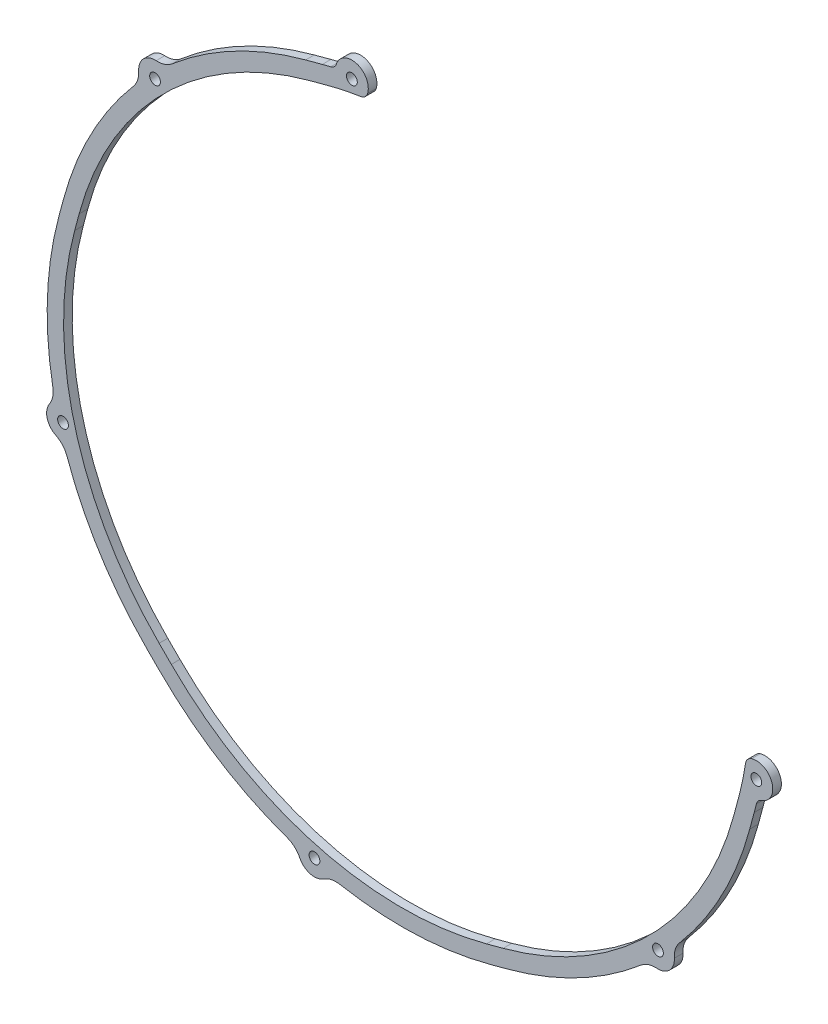
SolidWorks part; units mm, degrees
material "Hexcel AS4C (3000 丝)"
ref_plane "前视基准面" through (0, 0, 0) normal (0, 0, 1) x (1, 0, 0)
ref_plane "上视基准面" through (0, 0, 0) normal (0, 1, 0) x (1, 0, 0)
ref_plane "右视基准面" through (0, 0, 0) normal (1, 0, 0) x (0, 0, -1)
sketch "草图1" plane through (0, 0, 0) normal (0, 0, 1) x (1, 0, 0)
  line L10 (-6.2611, -107.9819) -> (-5.2259, -104.1182)
  line L11 (-7.9304, -103.3935) -> (-8.9657, -107.2573)
  line L12 (-62.4484, -160.7399) -> (-66.3121, -161.7752)
  line L13 (-139.3707, -142.1992) -> (-142.1992, -139.3707)
  line L14 (-161.7752, -66.3121) -> (-160.7399, -62.4484)
  line L15 (-107.2573, -8.9657) -> (-103.3935, -7.9304)
  line L16 (-104.1182, -5.2259) -> (-107.9819, -6.2611)
  line L17 (-163.4445, -61.7237) -> (-164.4798, -65.5874)
  line L18 (-144.1791, -141.3506) -> (-141.3506, -144.1791)
  line L19 (-65.5874, -164.4798) -> (-61.7237, -163.4445)
  line L20 (-6.2611, -107.9819) -> (-5.2259, -104.1182)
  line L21 (-7.9304, -103.3935) -> (-8.9657, -107.2573)
  line L22 (-62.4484, -160.7399) -> (-66.3121, -161.7752)
  line L23 (-139.3707, -142.1992) -> (-142.1992, -139.3707)
  line L24 (-161.7752, -66.3121) -> (-160.7399, -62.4484)
  line L25 (-107.2573, -8.9657) -> (-103.3935, -7.9304)
  line L26 (-104.1182, -5.2259) -> (-107.9819, -6.2611)
  line L27 (-163.4445, -61.7237) -> (-164.4798, -65.5874)
  line L28 (-144.1791, -141.3506) -> (-141.3506, -144.1791)
  line L29 (-65.5874, -164.4798) -> (-61.7237, -163.4445)
  circle A1 centre (-97.5152, -3.7585) radius 1.25
  circle A2 centre (-97.5152, -3.7585) radius 1.25
  circle A3 centre (-164.4798, -106.1888) radius 1.25
  circle A4 centre (-164.4798, -106.1888) radius 1.25
  circle A5 centre (-106.1888, -164.4798) radius 1.25
  circle A6 centre (-106.1888, -164.4798) radius 1.25
  circle A7 centre (-26.5618, -143.1438) radius 1.25
  circle A8 centre (-26.5618, -143.1438) radius 1.25
  circle A9 centre (-3.7585, -97.5152) radius 1.25
  circle A10 centre (-3.7585, -97.5152) radius 1.25
  circle A11 centre (-143.1438, -26.5618) radius 1.25
  circle A12 centre (-143.1438, -26.5618) radius 1.25
  arc A44 (-26.7497, -145.9375) -> (-23.7681, -142.9559) centre (-26.5618, -143.1438) ccw
  arc A45 (-22.3073, -138.5345) -> (-23.7681, -142.9559) centre (-17.6022, -142.5412) ccw
  arc A46 (-22.3073, -138.5345) -> (-6.2611, -107.9819) centre (-82.0244, -87.6812) ccw
  arc A47 (-5.2259, -104.1182) -> (-4.7329, -102.1799) centre (-80.9891, -83.8175) ccw
  arc A48 (-2.8846, -100.1753) -> (-4.7329, -102.1799) centre (-2.0107, -102.8354) ccw
  arc A49 (-2.8846, -100.1753) -> (-6.5155, -97.0262) centre (-3.7585, -97.5152) ccw
  arc A50 (-7.9304, -103.3935) -> (-6.5155, -97.0262) centre (-80.9891, -83.8175) ccw
  arc A51 (-62.4484, -160.7399) -> (-8.9657, -107.2573) centre (-82.0244, -87.6812) ccw
  arc A52 (-139.3707, -142.1992) -> (-66.3121, -161.7752) centre (-85.8881, -88.7165) ccw
  arc A53 (-161.7752, -66.3121) -> (-142.1992, -139.3707) centre (-88.7165, -85.8881) ccw
  arc A54 (-107.2573, -8.9657) -> (-160.7399, -62.4484) centre (-87.6812, -82.0244) ccw
  arc A55 (-97.0262, -6.5155) -> (-103.3935, -7.9304) centre (-83.8175, -80.9891) ccw
  arc A56 (-97.0262, -6.5155) -> (-100.1753, -2.8846) centre (-97.5152, -3.7585) ccw
  arc A57 (-102.1799, -4.7329) -> (-100.1753, -2.8846) centre (-102.8354, -2.0107) ccw
  arc A58 (-102.1799, -4.7329) -> (-104.1182, -5.2259) centre (-83.8175, -80.9891) ccw
  arc A59 (-107.9819, -6.2611) -> (-138.5345, -22.3073) centre (-87.6812, -82.0244) ccw
  arc A60 (-142.9559, -23.7681) -> (-138.5345, -22.3073) centre (-142.5412, -17.6022) ccw
  arc A61 (-142.9559, -23.7681) -> (-145.9375, -26.7497) centre (-143.1438, -26.5618) ccw
  arc A62 (-147.3984, -31.1711) -> (-145.9375, -26.7497) centre (-152.1034, -27.1645) ccw
  arc A63 (-147.3984, -31.1711) -> (-163.4445, -61.7237) centre (-87.6812, -82.0244) ccw
  arc A64 (-164.4798, -65.5874) -> (-165.8597, -100.0697) centre (-88.7165, -85.8881) ccw
  arc A65 (-166.8052, -104.6292) -> (-165.8597, -100.0697) centre (-171.9377, -101.1871) ccw
  arc A66 (-166.8052, -104.6292) -> (-165.7139, -108.7022) centre (-164.4798, -106.1888) ccw
  arc A67 (-162.6153, -112.178) -> (-165.7139, -108.7022) centre (-168.4377, -114.2494) ccw
  arc A68 (-162.6153, -112.178) -> (-144.1791, -141.3506) centre (-88.7165, -85.8881) ccw
  arc A69 (-141.3506, -144.1791) -> (-112.178, -162.6153) centre (-85.8881, -88.7165) ccw
  arc A70 (-108.7022, -165.7139) -> (-112.178, -162.6153) centre (-114.2494, -168.4377) ccw
  arc A71 (-108.7022, -165.7139) -> (-104.6292, -166.8052) centre (-106.1888, -164.4798) ccw
  arc A72 (-100.0697, -165.8597) -> (-104.6292, -166.8052) centre (-101.1871, -171.9377) ccw
  arc A73 (-100.0697, -165.8597) -> (-65.5874, -164.4798) centre (-85.8881, -88.7165) ccw
  arc A74 (-61.7237, -163.4445) -> (-31.1711, -147.3984) centre (-82.0244, -87.6812) ccw
  arc A75 (-26.7497, -145.9375) -> (-31.1711, -147.3984) centre (-27.1645, -152.1034) ccw
  arc A76 (-26.7497, -145.9375) -> (-23.7681, -142.9559) centre (-26.5618, -143.1438) ccw
  arc A77 (-22.3073, -138.5345) -> (-23.7681, -142.9559) centre (-17.6022, -142.5412) ccw
  arc A78 (-22.3073, -138.5345) -> (-6.2611, -107.9819) centre (-82.0244, -87.6812) ccw
  arc A79 (-5.2259, -104.1182) -> (-4.7329, -102.1799) centre (-80.9891, -83.8175) ccw
  arc A80 (-2.8846, -100.1753) -> (-4.7329, -102.1799) centre (-2.0107, -102.8354) ccw
  arc A81 (-2.8846, -100.1753) -> (-6.5155, -97.0262) centre (-3.7585, -97.5152) ccw
  arc A82 (-7.9304, -103.3935) -> (-6.5155, -97.0262) centre (-80.9891, -83.8175) ccw
  arc A83 (-62.4484, -160.7399) -> (-8.9657, -107.2573) centre (-82.0244, -87.6812) ccw
  arc A84 (-139.3707, -142.1992) -> (-66.3121, -161.7752) centre (-85.8881, -88.7165) ccw
  arc A85 (-161.7752, -66.3121) -> (-142.1992, -139.3707) centre (-88.7165, -85.8881) ccw
  arc A86 (-107.2573, -8.9657) -> (-160.7399, -62.4484) centre (-87.6812, -82.0244) ccw
  arc A87 (-97.0262, -6.5155) -> (-103.3935, -7.9304) centre (-83.8175, -80.9891) ccw
  arc A88 (-97.0262, -6.5155) -> (-100.1753, -2.8846) centre (-97.5152, -3.7585) ccw
  arc A89 (-102.1799, -4.7329) -> (-100.1753, -2.8846) centre (-102.8354, -2.0107) ccw
  arc A90 (-102.1799, -4.7329) -> (-104.1182, -5.2259) centre (-83.8175, -80.9891) ccw
  arc A91 (-107.9819, -6.2611) -> (-138.5345, -22.3073) centre (-87.6812, -82.0244) ccw
  arc A92 (-142.9559, -23.7681) -> (-138.5345, -22.3073) centre (-142.5412, -17.6022) ccw
  arc A93 (-142.9559, -23.7681) -> (-145.9375, -26.7497) centre (-143.1438, -26.5618) ccw
  arc A94 (-147.3984, -31.1711) -> (-145.9375, -26.7497) centre (-152.1034, -27.1645) ccw
  arc A95 (-147.3984, -31.1711) -> (-163.4445, -61.7237) centre (-87.6812, -82.0244) ccw
  arc A96 (-164.4798, -65.5874) -> (-165.8597, -100.0697) centre (-88.7165, -85.8881) ccw
  arc A97 (-166.8052, -104.6292) -> (-165.8597, -100.0697) centre (-171.9377, -101.1871) ccw
  arc A98 (-166.8052, -104.6292) -> (-165.7139, -108.7022) centre (-164.4798, -106.1888) ccw
  arc A99 (-162.6153, -112.178) -> (-165.7139, -108.7022) centre (-168.4377, -114.2494) ccw
  arc A100 (-162.6153, -112.178) -> (-144.1791, -141.3506) centre (-88.7165, -85.8881) ccw
  arc A101 (-141.3506, -144.1791) -> (-112.178, -162.6153) centre (-85.8881, -88.7165) ccw
  arc A102 (-108.7022, -165.7139) -> (-112.178, -162.6153) centre (-114.2494, -168.4377) ccw
  arc A103 (-108.7022, -165.7139) -> (-104.6292, -166.8052) centre (-106.1888, -164.4798) ccw
  arc A104 (-100.0697, -165.8597) -> (-104.6292, -166.8052) centre (-101.1871, -171.9377) ccw
  arc A105 (-100.0697, -165.8597) -> (-65.5874, -164.4798) centre (-85.8881, -88.7165) ccw
  arc A106 (-61.7237, -163.4445) -> (-31.1711, -147.3984) centre (-82.0244, -87.6812) ccw
  arc A107 (-26.7497, -145.9375) -> (-31.1711, -147.3984) centre (-27.1645, -152.1034) ccw
  dimension "D1" = 0
  dimension "D2" = 0
  dimension "D3" = 0
  dimension "D4" = 0
  dimension "D5" = 0
  dimension "D6" = 0
  dimension "D7" = 0
extrude "凸台-拉伸1" add sketch "草图1" along normal blind 2
sketch "草图2" plane through (0, 0, 0) normal (0, 0, -1) x (-1, 0, 0)
  line L0 (4.2599, -104.3771) -> (5.2952, -108.2408)
  line L1 (9.9316, -106.9984) -> (8.8964, -103.1347) construction
  line L2 (66.5709, -160.8093) -> (62.7072, -159.774) construction
  line L3 (141.4921, -138.6636) -> (138.6636, -141.4921) construction
  line L4 (159.774, -62.7072) -> (160.8093, -66.5709) construction
  line L5 (103.1347, -8.8964) -> (106.9984, -9.9316) construction
  line L6 (108.2408, -5.2952) -> (104.3771, -4.2599)
  line L7 (165.4457, -65.3286) -> (164.4104, -61.4649)
  line L8 (142.0578, -144.8862) -> (144.8862, -142.0578)
  line L9 (61.4649, -164.4104) -> (65.3286, -165.4457)
  line L10 (61.7237, -163.4445) -> (65.5874, -164.4798)
  line L11 (141.3506, -144.1791) -> (144.1791, -141.3506)
  line L12 (164.4798, -65.5874) -> (163.4445, -61.7237)
  line L13 (107.9819, -6.2611) -> (104.1182, -5.2259)
  line L14 (103.3935, -7.9304) -> (107.2573, -8.9657)
  line L15 (160.7399, -62.4484) -> (161.7752, -66.3121)
  line L16 (142.1992, -139.3707) -> (139.3707, -142.1992)
  line L17 (66.3121, -161.7752) -> (62.4484, -160.7399)
  line L18 (8.9657, -107.2573) -> (7.9304, -103.3935)
  line L19 (5.2259, -104.1182) -> (6.2611, -107.9819)
  line L20 (61.7237, -163.4445) -> (65.5874, -164.4798) construction
  line L21 (141.3506, -144.1791) -> (144.1791, -141.3506) construction
  line L22 (164.4798, -65.5874) -> (163.4445, -61.7237) construction
  line L23 (107.9819, -6.2611) -> (104.1182, -5.2259) construction
  line L24 (103.3935, -7.9304) -> (107.2573, -8.9657) construction
  line L25 (160.7399, -62.4484) -> (161.7752, -66.3121) construction
  line L26 (142.1992, -139.3707) -> (139.3707, -142.1992) construction
  line L27 (66.3121, -161.7752) -> (62.4484, -160.7399) construction
  line L28 (8.9657, -107.2573) -> (7.9304, -103.3935) construction
  line L29 (5.2259, -104.1182) -> (6.2611, -107.9819) construction
  line L30 (7.9304, -103.3935) -> (8.9657, -107.2573) construction
  line L31 (62.4484, -160.7399) -> (66.3121, -161.7752) construction
  line L32 (139.3707, -142.1992) -> (142.1992, -139.3707) construction
  line L33 (161.7752, -66.3121) -> (160.7399, -62.4484) construction
  line L34 (107.2573, -8.9657) -> (103.3935, -7.9304) construction
  line L35 (7.9304, -103.3935) -> (8.9657, -107.2573)
  line L36 (62.4484, -160.7399) -> (66.3121, -161.7752)
  line L37 (139.3707, -142.1992) -> (142.1992, -139.3707)
  line L38 (161.7752, -66.3121) -> (160.7399, -62.4484)
  line L39 (107.2573, -8.9657) -> (103.3935, -7.9304)
  circle A1 centre (97.5152, -3.7585) radius 1.25
  circle A2 centre (97.5152, -3.7585) radius 1.25
  circle A3 centre (164.4798, -106.1888) radius 1.25
  circle A4 centre (164.4798, -106.1888) radius 1.25
  circle A5 centre (106.1888, -164.4798) radius 1.25
  circle A6 centre (106.1888, -164.4798) radius 1.25
  circle A7 centre (26.5618, -143.1438) radius 1.25
  circle A8 centre (26.5618, -143.1438) radius 1.25
  circle A9 centre (3.7585, -97.5152) radius 1.25
  circle A10 centre (3.7585, -97.5152) radius 1.25
  circle A11 centre (143.1438, -26.5618) radius 1.25
  circle A12 centre (143.1438, -26.5618) radius 1.25
  arc A13 (30.5228, -148.1597) -> (26.8169, -146.9352) centre (27.1645, -152.1034) ccw
  arc A14 (22.7704, -142.8888) -> (26.8169, -146.9352) centre (26.5618, -143.1438) ccw
  arc A15 (22.7704, -142.8888) -> (21.5459, -139.1828) centre (17.6022, -142.5412) ccw
  arc A16 (5.2952, -108.2408) -> (21.5459, -139.1828) centre (82.0244, -87.6812) ccw
  arc A17 (3.7607, -102.4141) -> (4.2599, -104.3771) centre (80.9891, -83.8175) ccw
  arc A18 (3.7607, -102.4141) -> (2.5725, -101.1254) centre (2.0107, -102.8354) ccw
  arc A19 (7.5001, -96.8516) -> (2.5725, -101.1254) centre (3.7585, -97.5152) ccw construction
  arc A20 (7.5001, -96.8516) -> (8.8964, -103.1347) centre (80.9891, -83.8175) ccw construction
  arc A21 (9.9316, -106.9984) -> (62.7072, -159.774) centre (82.0244, -87.6812) ccw construction
  arc A22 (66.5709, -160.8093) -> (138.6636, -141.4921) centre (85.8881, -88.7165) ccw construction
  arc A23 (141.4921, -138.6636) -> (160.8093, -66.5709) centre (88.7165, -85.8881) ccw construction
  arc A24 (159.774, -62.7072) -> (106.9984, -9.9316) centre (87.6812, -82.0244) ccw construction
  arc A25 (103.1347, -8.8964) -> (96.8516, -7.5001) centre (83.8175, -80.9891) ccw construction
  arc A26 (101.1254, -2.5725) -> (96.8516, -7.5001) centre (97.5152, -3.7585) ccw construction
  arc A27 (101.1254, -2.5725) -> (102.4141, -3.7607) centre (102.8354, -2.0107) ccw
  arc A28 (104.3771, -4.2599) -> (102.4141, -3.7607) centre (83.8175, -80.9891) ccw
  arc A29 (139.1828, -21.5459) -> (108.2408, -5.2952) centre (87.6812, -82.0244) ccw
  arc A30 (139.1828, -21.5459) -> (142.8888, -22.7704) centre (142.5412, -17.6022) ccw
  arc A31 (146.9352, -26.8169) -> (142.8888, -22.7704) centre (143.1438, -26.5618) ccw
  arc A32 (146.9352, -26.8169) -> (148.1597, -30.5228) centre (152.1034, -27.1645) ccw
  arc A33 (164.4104, -61.4649) -> (148.1597, -30.5228) centre (87.6812, -82.0244) ccw
  arc A34 (166.8432, -100.2505) -> (165.4457, -65.3286) centre (88.7165, -85.8881) ccw
  arc A35 (166.8432, -100.2505) -> (167.6357, -104.0722) centre (171.9377, -101.1871) ccw
  arc A36 (166.1546, -109.5998) -> (167.6357, -104.0722) centre (164.4798, -106.1888) ccw
  arc A37 (166.1546, -109.5998) -> (163.5575, -112.5132) centre (168.4377, -114.2494) ccw
  arc A38 (144.8862, -142.0578) -> (163.5575, -112.5132) centre (88.7165, -85.8881) ccw
  arc A39 (112.5132, -163.5575) -> (142.0578, -144.8862) centre (85.8881, -88.7165) ccw
  arc A40 (112.5132, -163.5575) -> (109.5998, -166.1546) centre (114.2494, -168.4377) ccw
  arc A41 (104.0722, -167.6357) -> (109.5998, -166.1546) centre (106.1888, -164.4798) ccw
  arc A42 (104.0722, -167.6357) -> (100.2505, -166.8432) centre (101.1871, -171.9377) ccw
  arc A43 (65.3286, -165.4457) -> (100.2505, -166.8432) centre (85.8881, -88.7165) ccw
  arc A44 (31.1711, -147.3984) -> (26.7497, -145.9375) centre (27.1645, -152.1034) ccw
  arc A45 (31.1711, -147.3984) -> (61.7237, -163.4445) centre (82.0244, -87.6812) ccw
  arc A46 (65.5874, -164.4798) -> (100.0697, -165.8597) centre (85.8881, -88.7165) ccw
  arc A47 (104.6292, -166.8052) -> (100.0697, -165.8597) centre (101.1871, -171.9377) ccw
  arc A48 (104.6292, -166.8052) -> (108.7022, -165.7139) centre (106.1888, -164.4798) ccw
  arc A49 (112.178, -162.6153) -> (108.7022, -165.7139) centre (114.2494, -168.4377) ccw
  arc A50 (112.178, -162.6153) -> (141.3506, -144.1791) centre (85.8881, -88.7165) ccw
  arc A51 (144.1791, -141.3506) -> (162.6153, -112.178) centre (88.7165, -85.8881) ccw
  arc A52 (165.7139, -108.7022) -> (162.6153, -112.178) centre (168.4377, -114.2494) ccw
  arc A53 (165.7139, -108.7022) -> (166.8052, -104.6292) centre (164.4798, -106.1888) ccw
  arc A54 (165.8597, -100.0697) -> (166.8052, -104.6292) centre (171.9377, -101.1871) ccw
  arc A55 (165.8597, -100.0697) -> (164.4798, -65.5874) centre (88.7165, -85.8881) ccw
  arc A56 (163.4445, -61.7237) -> (147.3984, -31.1711) centre (87.6812, -82.0244) ccw
  arc A57 (145.9375, -26.7497) -> (147.3984, -31.1711) centre (152.1034, -27.1645) ccw
  arc A58 (145.9375, -26.7497) -> (142.9559, -23.7681) centre (143.1438, -26.5618) ccw
  arc A59 (138.5345, -22.3073) -> (142.9559, -23.7681) centre (142.5412, -17.6022) ccw
  arc A60 (138.5345, -22.3073) -> (107.9819, -6.2611) centre (87.6812, -82.0244) ccw
  arc A61 (104.1182, -5.2259) -> (102.1799, -4.7329) centre (83.8175, -80.9891) ccw
  arc A62 (100.1753, -2.8846) -> (102.1799, -4.7329) centre (102.8354, -2.0107) ccw
  arc A63 (100.1753, -2.8846) -> (97.0262, -6.5155) centre (97.5152, -3.7585) ccw
  arc A64 (103.3935, -7.9304) -> (97.0262, -6.5155) centre (83.8175, -80.9891) ccw
  arc A65 (160.7399, -62.4484) -> (107.2573, -8.9657) centre (87.6812, -82.0244) ccw
  arc A66 (142.1992, -139.3707) -> (161.7752, -66.3121) centre (88.7165, -85.8881) ccw
  arc A67 (66.3121, -161.7752) -> (139.3707, -142.1992) centre (85.8881, -88.7165) ccw
  arc A68 (8.9657, -107.2573) -> (62.4484, -160.7399) centre (82.0244, -87.6812) ccw
  arc A69 (6.5155, -97.0262) -> (7.9304, -103.3935) centre (80.9891, -83.8175) ccw
  arc A70 (6.5155, -97.0262) -> (2.8846, -100.1753) centre (3.7585, -97.5152) ccw
  arc A71 (4.7329, -102.1799) -> (2.8846, -100.1753) centre (2.0107, -102.8354) ccw
  arc A72 (4.7329, -102.1799) -> (5.2259, -104.1182) centre (80.9891, -83.8175) ccw
  arc A73 (6.2611, -107.9819) -> (22.3073, -138.5345) centre (82.0244, -87.6812) ccw
  arc A74 (23.7681, -142.9559) -> (22.3073, -138.5345) centre (17.6022, -142.5412) ccw
  arc A75 (23.7681, -142.9559) -> (26.7497, -145.9375) centre (26.5618, -143.1438) ccw
  arc A76 (31.1711, -147.3984) -> (26.7497, -145.9375) centre (27.1645, -152.1034) ccw construction
  arc A77 (31.1711, -147.3984) -> (61.7237, -163.4445) centre (82.0244, -87.6812) ccw construction
  arc A78 (65.5874, -164.4798) -> (100.0697, -165.8597) centre (85.8881, -88.7165) ccw construction
  arc A79 (104.6292, -166.8052) -> (100.0697, -165.8597) centre (101.1871, -171.9377) ccw construction
  arc A80 (104.6292, -166.8052) -> (108.7022, -165.7139) centre (106.1888, -164.4798) ccw construction
  arc A81 (112.178, -162.6153) -> (108.7022, -165.7139) centre (114.2494, -168.4377) ccw construction
  arc A82 (112.178, -162.6153) -> (141.3506, -144.1791) centre (85.8881, -88.7165) ccw construction
  arc A83 (144.1791, -141.3506) -> (162.6153, -112.178) centre (88.7165, -85.8881) ccw construction
  arc A84 (165.7139, -108.7022) -> (162.6153, -112.178) centre (168.4377, -114.2494) ccw construction
  arc A85 (165.7139, -108.7022) -> (166.8052, -104.6292) centre (164.4798, -106.1888) ccw construction
  arc A86 (165.8597, -100.0697) -> (166.8052, -104.6292) centre (171.9377, -101.1871) ccw construction
  arc A87 (165.8597, -100.0697) -> (164.4798, -65.5874) centre (88.7165, -85.8881) ccw construction
  arc A88 (163.4445, -61.7237) -> (147.3984, -31.1711) centre (87.6812, -82.0244) ccw construction
  arc A89 (145.9375, -26.7497) -> (147.3984, -31.1711) centre (152.1034, -27.1645) ccw construction
  arc A90 (145.9375, -26.7497) -> (142.9559, -23.7681) centre (143.1438, -26.5618) ccw construction
  arc A91 (138.5345, -22.3073) -> (142.9559, -23.7681) centre (142.5412, -17.6022) ccw construction
  arc A92 (138.5345, -22.3073) -> (107.9819, -6.2611) centre (87.6812, -82.0244) ccw construction
  arc A93 (104.1182, -5.2259) -> (102.1799, -4.7329) centre (83.8175, -80.9891) ccw construction
  arc A94 (100.1753, -2.8846) -> (102.1799, -4.7329) centre (102.8354, -2.0107) ccw construction
  arc A95 (100.1753, -2.8846) -> (97.0262, -6.5155) centre (97.5152, -3.7585) ccw construction
  arc A96 (103.3935, -7.9304) -> (97.0262, -6.5155) centre (83.8175, -80.9891) ccw construction
  arc A97 (160.7399, -62.4484) -> (107.2573, -8.9657) centre (87.6812, -82.0244) ccw construction
  arc A98 (142.1992, -139.3707) -> (161.7752, -66.3121) centre (88.7165, -85.8881) ccw construction
  arc A99 (66.3121, -161.7752) -> (139.3707, -142.1992) centre (85.8881, -88.7165) ccw construction
  arc A100 (8.9657, -107.2573) -> (62.4484, -160.7399) centre (82.0244, -87.6812) ccw construction
  arc A101 (6.5155, -97.0262) -> (7.9304, -103.3935) centre (80.9891, -83.8175) ccw construction
  arc A102 (6.5155, -97.0262) -> (2.8846, -100.1753) centre (3.7585, -97.5152) ccw construction
  arc A103 (4.7329, -102.1799) -> (2.8846, -100.1753) centre (2.0107, -102.8354) ccw construction
  arc A104 (4.7329, -102.1799) -> (5.2259, -104.1182) centre (80.9891, -83.8175) ccw construction
  arc A105 (6.2611, -107.9819) -> (22.3073, -138.5345) centre (82.0244, -87.6812) ccw construction
  arc A106 (23.7681, -142.9559) -> (22.3073, -138.5345) centre (17.6022, -142.5412) ccw construction
  arc A107 (23.7681, -142.9559) -> (26.7497, -145.9375) centre (26.5618, -143.1438) ccw construction
  arc A108 (30.5228, -148.1597) -> (61.4649, -164.4104) centre (82.0244, -87.6812) ccw
  arc A109 (6.5155, -97.0262) -> (7.9304, -103.3935) centre (80.9891, -83.8175) ccw construction
  arc A110 (8.9657, -107.2573) -> (62.4484, -160.7399) centre (82.0244, -87.6812) ccw construction
  arc A111 (66.3121, -161.7752) -> (139.3707, -142.1992) centre (85.8881, -88.7165) ccw construction
  arc A112 (142.1992, -139.3707) -> (161.7752, -66.3121) centre (88.7165, -85.8881) ccw construction
  arc A113 (160.7399, -62.4484) -> (107.2573, -8.9657) centre (87.6812, -82.0244) ccw construction
  arc A114 (103.3935, -7.9304) -> (97.0262, -6.5155) centre (83.8175, -80.9891) ccw construction
  arc A115 (6.5155, -97.0262) -> (7.9304, -103.3935) centre (80.9891, -83.8175) ccw
  arc A116 (8.9657, -107.2573) -> (62.4484, -160.7399) centre (82.0244, -87.6812) ccw
  arc A117 (66.3121, -161.7752) -> (139.3707, -142.1992) centre (85.8881, -88.7165) ccw
  arc A118 (142.1992, -139.3707) -> (161.7752, -66.3121) centre (88.7165, -85.8881) ccw
  arc A119 (160.7399, -62.4484) -> (107.2573, -8.9657) centre (87.6812, -82.0244) ccw
  arc A120 (103.3935, -7.9304) -> (97.0262, -6.5155) centre (83.8175, -80.9891) ccw
  arc A121 (101.1254, -2.5725) -> (93.8797, -4.8645) centre (97.5152, -3.7585) ccw
  arc A122 (97.0262, -6.5155) -> (95.4846, -6.2585) centre (83.8175, -80.9891) ccw
  arc A123 (93.8797, -4.8645) -> (95.4846, -6.2585) centre (95.7931, -4.2824) ccw
  arc A124 (6.5155, -97.0262) -> (6.2585, -95.4846) centre (80.9891, -83.8175) cw
  arc A125 (2.5725, -101.1254) -> (4.8645, -93.8797) centre (3.7585, -97.5152) cw
  arc A126 (6.2585, -95.4846) -> (4.8645, -93.8797) centre (4.2824, -95.7931) ccw
  point P184 (94.5352, -6.1164)
  point P194 (6.1164, -94.5352)
  dimension "D9" = 2
  dimension "D10" = 2
  dimension "D1" = 0
  dimension "D2" = 0
  dimension "D3" = 0
  dimension "D4" = 0
  dimension "D5" = 0
  dimension "D6" = 0
  dimension "D7" = 0
  dimension "D8" = 1
extrude "凸台-拉伸2" add sketch "草图2" against normal up to surface (2 mm away) up to face at (-2.5085, -97.5152, 2)
